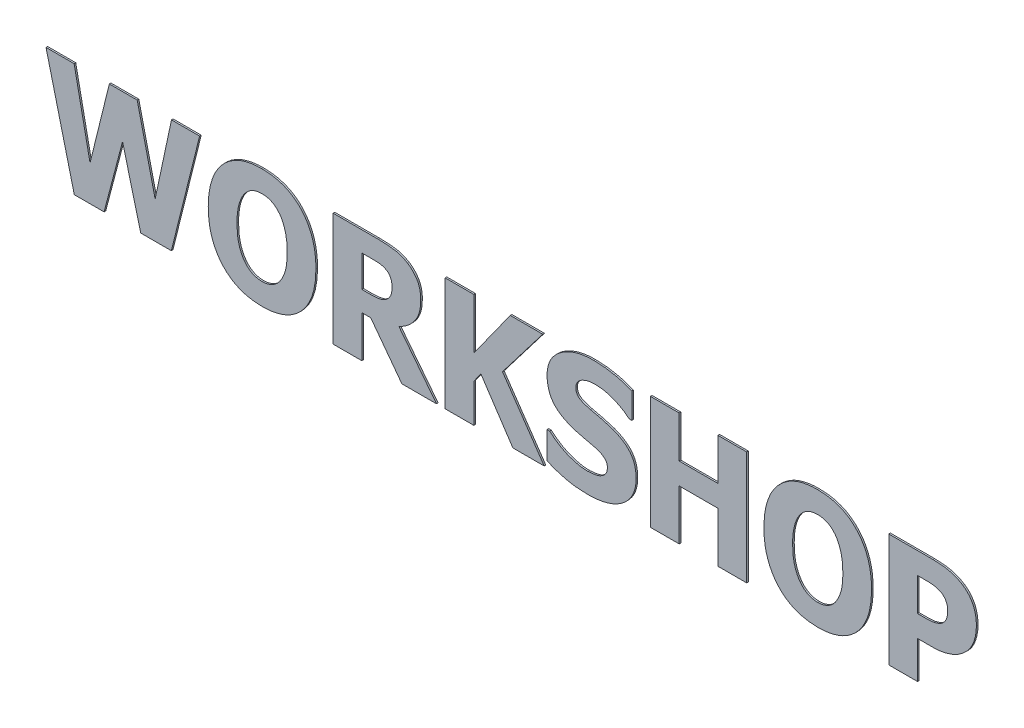
SolidWorks part; units mm, degrees
ref_plane "Front Plane" through (0, 0, 0) normal (0, 0, 1) x (1, 0, 0)
ref_plane "Top Plane" through (0, 0, 0) normal (0, 1, 0) x (1, 0, 0)
ref_plane "Right Plane" through (0, 0, 0) normal (1, 0, 0) x (0, 0, -1)
sketch "Sketch1" plane through (0, 0, 0) normal (0, 0, 1) x (1, 0, 0)
  line L0 (0, 0) -> (1099.0557, 0) construction
  text T0 "WORKSHOP" font "Tahoma" height 140
  point P3 (341.1578, 0)
  point P4 (219.9575, 0)
  point P5 (461.6053, 0)
  point P6 (583.9649, 0)
  point P7 (694.1779, 0)
  point P8 (815.7067, 0)
  point P9 (960.0414, 0)
  point P10 (1099.0557, 0)
extrude "Boss-Extrude1" add sketch "Sketch1" along normal blind 2
